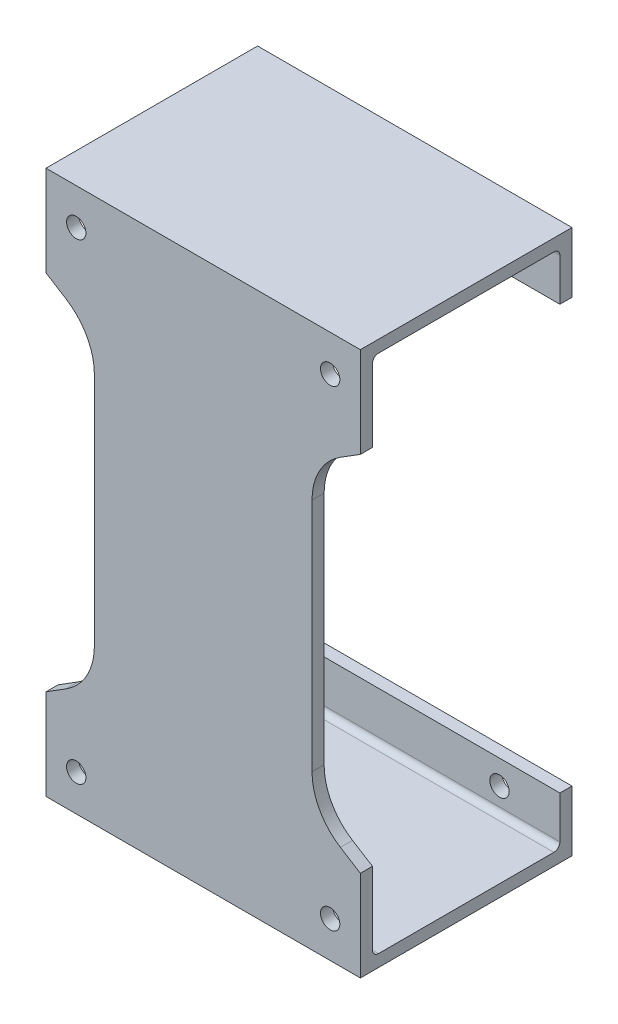
SolidWorks part; units mm, degrees
ref_plane "Top Plane" through (0, 0, 0) normal (0, 0, 1) x (1, 0, 0)
ref_plane "Right Plane" through (0, 0, 0) normal (0, 1, 0) x (1, 0, 0)
ref_plane "Front Plane" through (0, 0, 0) normal (1, 0, 0) x (0, 0, -1)
sketch "Sketch1" plane through (0, 0, 0) normal (1, 0, 0) x (0, 0, -1)
  line L0 (0, -45) -> (0, 45)
  line L1 (0, -45) -> (35, -45)
  line L2 (35, -45) -> (35, -35)
  line L3 (-52.6834, 0) -> (59.8675, 0) construction
  line L4 (35, 45) -> (35, 35)
  line L5 (0, 45) -> (35, 45)
  line L6 (33, 43) -> (33, 35)
  line L7 (2, 43) -> (33, 43)
  line L8 (2, -43) -> (2, 43)
  line L9 (2, -43) -> (33, -43)
  line L10 (33, -43) -> (33, -35)
  line L11 (33, -35) -> (35, -35)
  line L12 (33, 35) -> (35, 35)
  point P12 (0, 0)
  dimension "D1" = 35
  dimension "D2" = 10
  dimension "D3" = 90
  dimension "D4" = 2
extrude "Boss-Extrude1" add sketch "Sketch1" along normal mid plane 52
sketch "Sketch2" plane through (0, 0, 0) normal (0, 0, 1) x (1, 0, 0)
  line L0 (-30.8424, 0) -> (30.398, 0) construction
  line L1 (0, -48.7968) -> (0, 47.6414) construction
  circle A0 centre (-21, -39) radius 1.6
  circle A1 centre (-21, 39) radius 1.6
  circle A2 centre (21, 39) radius 1.6
  circle A3 centre (21, -39) radius 1.6
  dimension "D1" = 78
  dimension "D3" = 3.2
  dimension "D2" = 42
extrude "Cut-Extrude1" cut sketch "Sketch2" against normal up to next
sketch "Sketch3" plane through (0, 0, 0) normal (0, 0, 1) x (1, 0, 0)
  line L0 (26, 45) -> (26, -45) construction
  circle A0 centre (0, 0) radius 14
  dimension "D1" = 12
extrude "Cut-Extrude2" [suppressed] cut sketch "Sketch3" against normal up to next
sketch "Sketch4" plane through (0, -45, 0) normal (0, -1, 0) x (1, 0, 0)
  line L0 (0, 0) -> (0, -35) construction
  line L3 (26, 0) -> (26, -35) construction
  line L4 (26, -35) -> (-26, -35) construction
  circle A0 centre (-13, -17.5) radius 9
  circle A1 centre (13, -17.5) radius 9
  point P9 (0, -17.5)
  dimension "D1" = 8
  dimension "D2" = 4
extrude "Cut-Extrude3" [suppressed] cut sketch "Sketch4" against normal through all
sketch "Sketch5" plane through (0, 0, 0) normal (0, 0, 1) x (1, 0, 0)
  line L0 (-30.6647, 0) -> (33.5216, 0) construction
  line L1 (0, -51.5205) -> (0, 55.9011) construction
  line L6 (26, -45) -> (-26, -45) construction
  circle A0 centre (-12.4, -36) radius 5
  circle A1 centre (-12.4, 36) radius 5
  circle A2 centre (12.4, 36) radius 5
  circle A3 centre (12.4, -36) radius 5
  circle A6 centre (-21, -39) radius 1.6 construction
  dimension "D1" = 4
  dimension "D2" = 2
  dimension "D3" = 10
extrude "Cut-Extrude4" [suppressed] cut sketch "Sketch5" against normal up to next
sketch "Sketch6" plane through (0, 0, -33) normal (0, 0, 1) x (1, 0, 0)
  line L0 (0, 47.5711) -> (0, -51.6381) construction
  line L1 (-35.4935, 0) -> (38.6978, 0) construction
  circle A0 centre (16, -39) radius 1.6
  circle A1 centre (-16, -39) radius 1.6
  circle A2 centre (-16, 39) radius 1.6
  circle A3 centre (16, 39) radius 1.6
  dimension "D1" = 3.2
  dimension "D2" = 32
  dimension "D3" = 78
extrude "Cut-Extrude5" cut sketch "Sketch6" against normal up to next
fillet "Fillet1" radius 1 4 edges at (0, -43, -2) (0, 43, -2) (0, -43, -33) (0, 43, -33)
sketch "Sketch7" plane through (0, 0, 0) normal (0, 0, 1) x (1, 0, 0)
  line L0 (-26, 0) -> (26, 0) construction
  line L2 (-26, 45) -> (-26, -45) construction
  line L3 (26, 45) -> (26, -45) construction
  line L4 (-26, 30) -> (-18, 25)
  line L5 (-18, 25) -> (-18, -25)
  line L6 (-26, 30) -> (-26, -30)
  line L7 (-26, -30) -> (-18, -25)
  line L8 (0, 45) -> (0, -45) construction
  line L9 (26, 45) -> (-26, 45) construction
  line L10 (26, -45) -> (-26, -45) construction
  line L11 (26, -30) -> (18, -25)
  line L12 (26, 30) -> (26, -30)
  line L13 (18, 25) -> (18, -25)
  line L14 (26, 30) -> (18, 25)
  point P11 (-18, 0)
  point P17 (18, 0)
  dimension "D1" = 8
  dimension "D2" = 60
  dimension "D3" = 50
extrude "Cut-Extrude6" cut sketch "Sketch7" against normal up to next
fillet "Fillet2" radius 10 4 edges at (18, -25, -1) (18, 25, -1) (-18, -25, -1) (-18, 25, -1)
